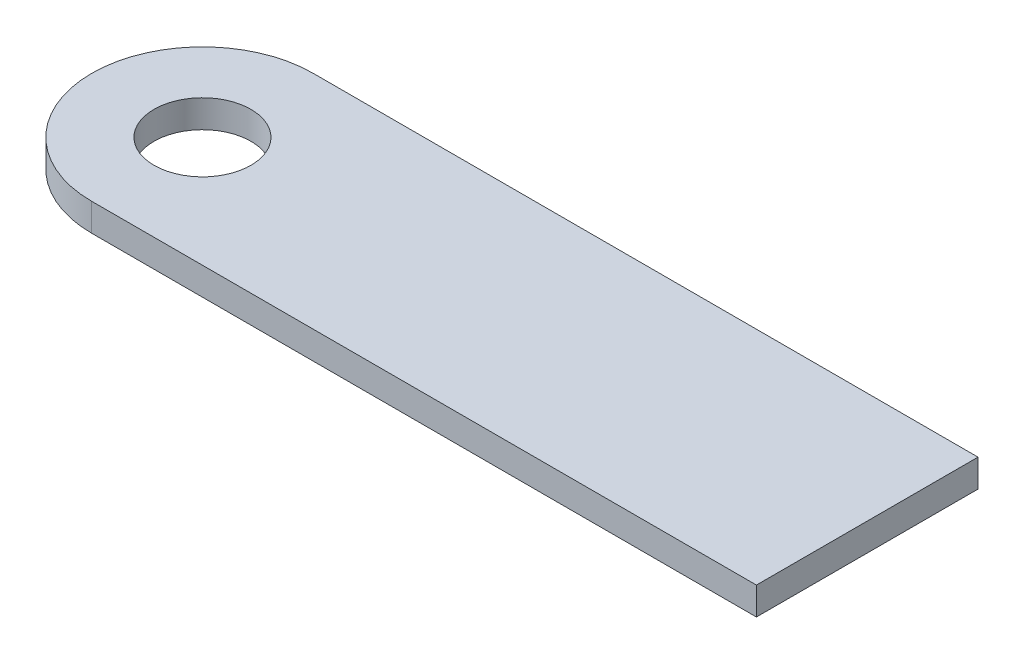
SolidWorks part; units mm, degrees
material "1060 Alloy"
ref_plane "Front Plane" through (0, 0, 0) normal (0, 0, 1) x (1, 0, 0)
ref_plane "Top Plane" through (0, 0, 0) normal (0, 1, 0) x (1, 0, 0)
ref_plane "Right Plane" through (0, 0, 0) normal (1, 0, 0) x (0, 0, -1)
sketch "Sketch1" plane through (0, 0, 0) normal (0, 1, 0) x (1, 0, 0)
  line L1 (38.1, -12.7) -> (-38.1, -12.7)
  line L2 (38.1, -12.7) -> (38.1, 12.7)
  line L3 (38.1, 12.7) -> (-38.1, 12.7)
  line L4 (-38.1, -12.7) -> (-38.1, 12.7) construction
  line L5 (38.1, -12.7) -> (-38.1, 12.7) construction
  line L6 (38.1, 12.7) -> (-38.1, -12.7) construction
  arc A0 (-38.1, 12.7) -> (-38.1, -12.7) centre (-38.1, 0) ccw
  circle A1 centre (-38.1, 0) radius 5.5562
  point P0 (0, 0)
  dimension "D3" = 11.1125
  dimension "D1" = 76.2
  dimension "D2" = 25.4
extrude "Boss-Extrude1" add sketch "Sketch1" along normal blind 3.175
